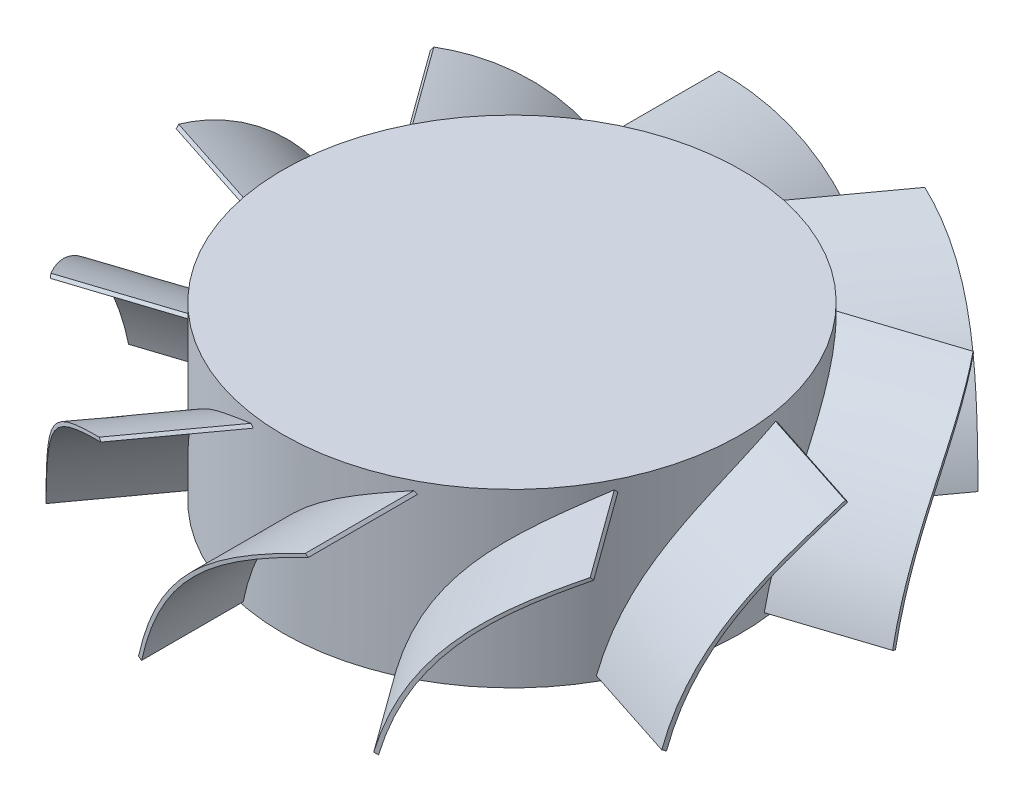
SolidWorks part; units mm, degrees
ref_plane "Front Plane" through (0, 0, 0) normal (0, 0, 1) x (1, 0, 0)
ref_plane "Top Plane" through (0, 0, 0) normal (0, 1, 0) x (1, 0, 0)
ref_plane "Right Plane" through (0, 0, 0) normal (1, 0, 0) x (0, 0, -1)
sketch "Sketch1" plane through (0, 0, 0) normal (0, 1, 0) x (1, 0, 0)
  circle A0 centre (0, 0) radius 8
  dimension "D1" = 16
extrude "Boss-Extrude1" add sketch "Sketch1" along normal blind 6
sketch "Sketch2" plane through (0, 0, 0) normal (0, 0, 1) x (1, 0, 0)
  line L0 (8, 6) -> (-8, 6) construction
  line L1 (8, 6) -> (-8, 6)
  line L2 (-8, 0) -> (8, 0) construction
  line L3 (-8, 0) -> (8, 0)
  line L4 (-1.6515, 0.1725) -> (-1.5292, 0.1076)
  line L5 (3.6795, 5.6975) -> (3.7623, 5.6029)
  spline S0 degree 2 poles (-1.6515, 0.1725) (-0.6222, 4.3386) (3.6795, 5.6975) knots 0 0 0 1 1 1
  spline S1 degree 2 poles (-1.5292, 0.1076) (-0.5128, 4.2681) (3.7623, 5.6029) knots 0 0 0 1 1 1
  point P9 (3.7623, 5.6029)
  point P11 (3.6795, 5.6975)
extrude "Boss-Extrude2" add sketch "Sketch2" along normal blind 11.5 contours S0 L5 S1 L4
pattern_circular "CirPattern1" count 10 over 360 about axis through (0, 0, 0) along (0, 1, 0) of "Boss-Extrude2"
sketch "Sketch3" plane through (0, 6, 0) normal (0, 1, 0) x (1, 0, 0)
  circle A0 centre (0, 0) radius 11.5
  circle A1 centre (0, 0) radius 12.5
  dimension "D1" = 23
  dimension "D2" = 25
extrude "Cut-Extrude1" cut sketch "Sketch3" against normal through all
